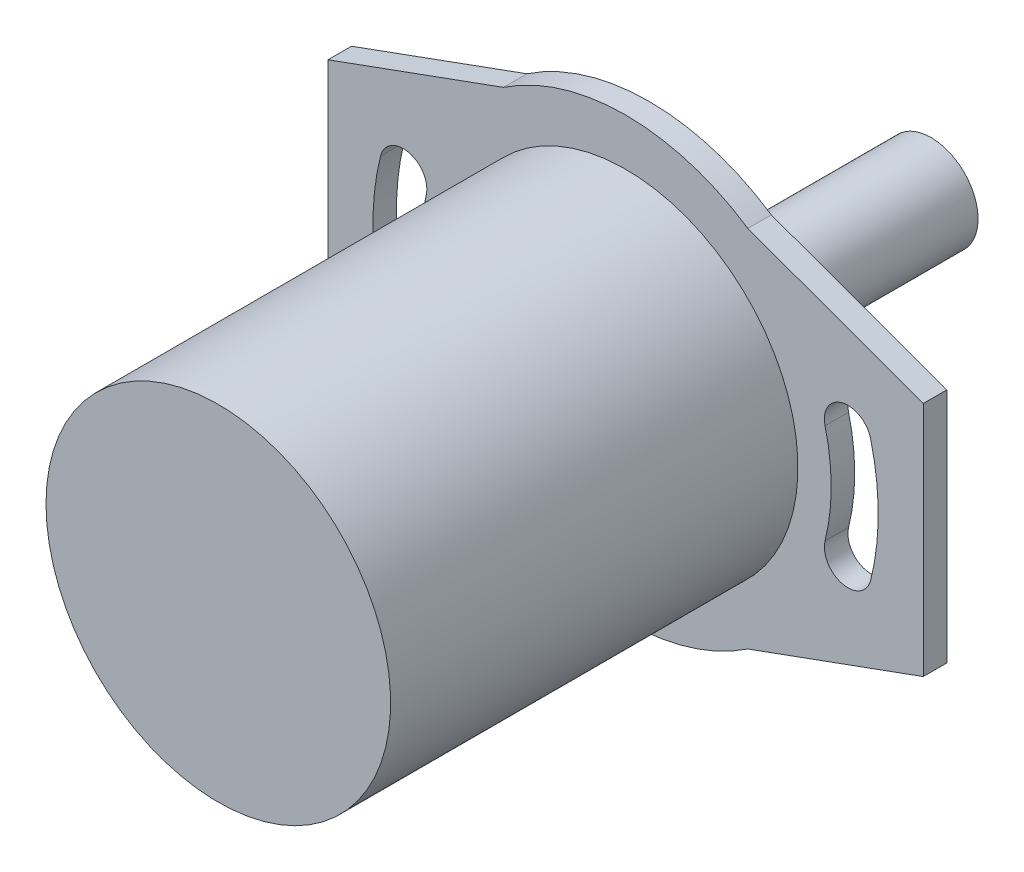
SolidWorks part; units mm, degrees
ref_plane "Plan de face" through (0, 0, 0) normal (0, 0, 1) x (1, 0, 0)
ref_plane "Plan de dessus" through (0, 0, 0) normal (0, 1, 0) x (1, 0, 0)
ref_plane "Plan de droite" through (0, 0, 0) normal (1, 0, 0) x (0, 0, -1)
sketch "Esquisse1" plane through (0, 0, 0) normal (0, 0, 1) x (1, 0, 0)
  circle A0 centre (0, 0) radius 11
  dimension "D1" = 22
extrude "Boss.-Extru.1" add sketch "Esquisse1" along normal blind 26
sketch "Esquisse2" plane through (0, 0, 0) normal (0, 0, -1) x (-1, 0, 0)
  line L0 (-7.8, 11.6258) -> (-19, 7.5494)
  line L1 (-19, 7.5494) -> (-19, 0)
  line L2 (-19, 0) -> (19, 0)
  line L3 (19, 0) -> (19, 7.5494)
  line L4 (19, 7.5494) -> (7.8, 11.6258)
  arc A0 (-7.8, 11.6258) -> (7.8, 11.6258) centre (0, 0) cw
  dimension "D1" = 14
  dimension "D2" = 38
  dimension "D3" = 110
  dimension "D4" = 110
  dimension "D5" = 11.2
extrude "Boss.-Extru.2" add sketch "Esquisse2" along normal blind 1.5
mirror "Symétrie1" about plane through (19, 0, -1.5) normal (0, 1, 0) of "Boss.-Extru.2"
sketch "Esquisse3" plane through (0, 0, -1.5) normal (0, 0, -1) x (-1, 0, 0)
  line L0 (0, 15.125) -> (0, -15.125) construction
  arc A1 (-14.1889, -3.5446) -> (-14.1889, 3.5446) centre (0.015, 0) cw construction
  arc A2 (-15.6443, 3.9078) -> (-15.6443, -3.9078) centre (0.015, 0) ccw
  arc A3 (-12.7336, 3.1814) -> (-12.7336, -3.1814) centre (0.015, 0) ccw
  arc A4 (-12.7336, 3.1814) -> (-15.6443, 3.9078) centre (-14.1889, 3.5446) ccw
  arc A5 (-15.6443, -3.9078) -> (-12.7336, -3.1814) centre (-14.1889, -3.5446) ccw
  arc A6 (14.1889, -3.5446) -> (14.1889, 3.5446) centre (0.015, 0) ccw construction
  arc A7 (15.6441, 3.9085) -> (15.6441, -3.9085) centre (0.015, 0) cw
  arc A8 (12.7338, 3.1807) -> (12.7338, -3.1807) centre (0.015, 0) cw
  arc A9 (12.7338, 3.1807) -> (15.6441, 3.9085) centre (14.1889, 3.5446) cw
  arc A10 (15.6441, -3.9085) -> (12.7338, -3.1807) centre (14.1889, -3.5446) cw
  circle A11 centre (0, 0) radius 13.125 construction
  point P6 (-14.6246, 0)
  point P11 (12.6044, -3.6598)
  point P12 (-14.0112, 4.1926)
  point P13 (0, 0)
  point P14 (-13.8258, 5)
  point P15 (-13.8258, -5)
  point P20 (14.6254, 0)
  point P26 (-12.7336, 3.1807)
  point P27 (-15.6443, 3.9085)
  dimension "D1" = 26.25
  dimension "D2" = 3
  dimension "D3" = 10
extrude "Enlèv. mat.-Extru.1" cut sketch "Esquisse3" against normal blind 1.5
sketch "Esquisse4" plane through (0, 0, -1.5) normal (0, 0, -1) x (-1, 0, 0)
  circle A0 centre (0, 0) radius 3
  dimension "D1" = 6
extrude "Boss.-Extru.3" add sketch "Esquisse4" along normal blind 18
